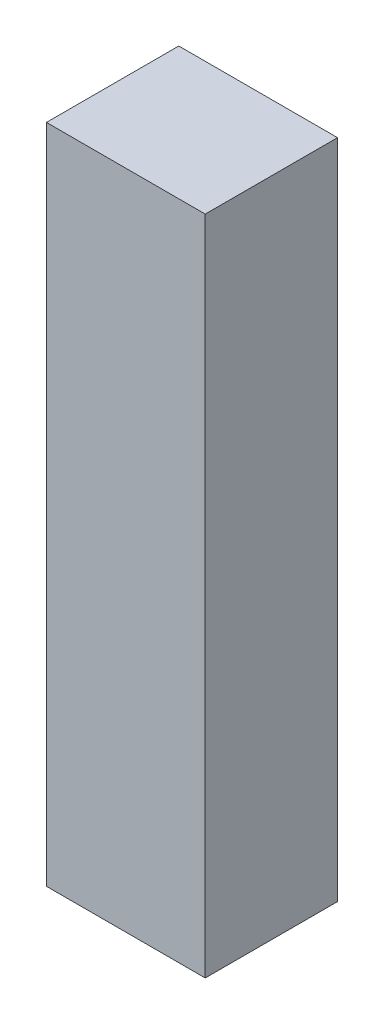
SolidWorks part; units mm, degrees
material "Copper"
ref_plane "Front Plane" through (0, 0, 0) normal (0, 0, 1) x (1, 0, 0)
ref_plane "Top Plane" through (0, 0, 0) normal (0, 1, 0) x (1, 0, 0)
ref_plane "Right Plane" through (0, 0, 0) normal (1, 0, 0) x (0, 0, -1)
sketch "Sketch2" plane through (0, 0, 0) normal (0, 0, 1) x (1, 0, 0)
  line L1 (-12, 50) -> (12, 50)
  line L2 (-12, 50) -> (-12, -50)
  line L3 (-12, -50) -> (12, -50)
  line L4 (12, 50) -> (12, -50)
  line L5 (0, -50) -> (0, 50) construction
  line L6 (-12, 0) -> (12, 0) construction
  point P0 (0, 0)
  dimension "D1" = 24
  dimension "D2" = 100
extrude "Boss-Extrude1" add sketch "Sketch2" along normal blind 20
sketch "Sketch3" plane through (0, 0, 0) normal (0, 0, -1) x (-1, 0, 0)
  line L1 (-12, 50) -> (12, 50)
  line L2 (-12, 50) -> (-12, -50)
  line L3 (-12, -50) -> (12, -50)
  line L4 (12, 50) -> (12, -50)
  line L5 (0, -50) -> (0, 50) construction
  line L6 (-12, 0) -> (12, 0) construction
  point P0 (0, 0)
